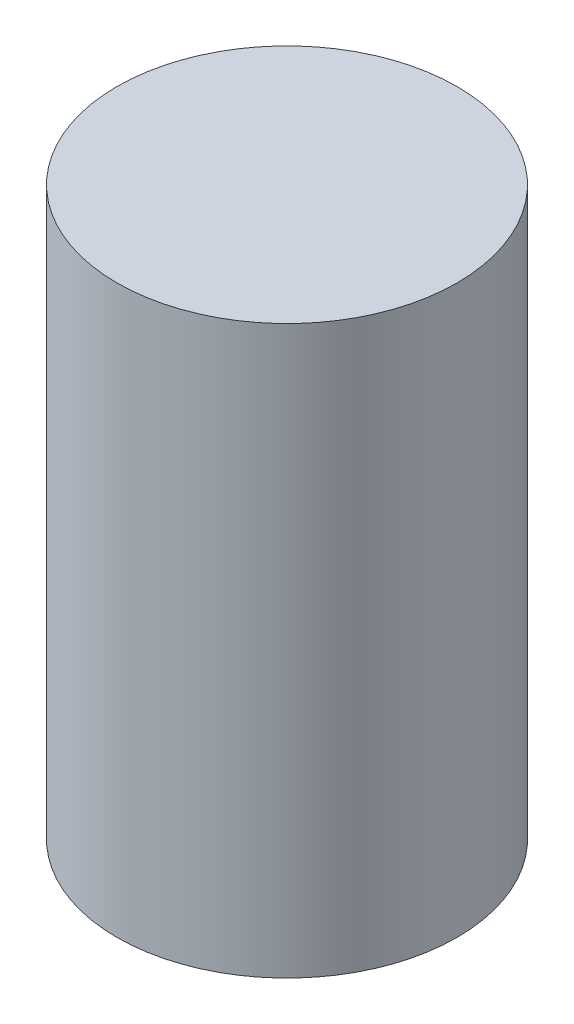
SolidWorks part; units mm, degrees
material "AISI 304"
ref_plane "前视基准面" through (0, 0, 0) normal (0, 0, 1) x (1, 0, 0)
ref_plane "上视基准面" through (0, 0, 0) normal (0, 1, 0) x (1, 0, 0)
ref_plane "右视基准面" through (0, 0, 0) normal (1, 0, 0) x (0, 0, -1)
sketch "草图1" plane through (0, 0, 0) normal (0, 1, 0) x (1, 0, 0)
  circle A0 centre (0, 0) radius 1.5
  dimension "D1" = 3
extrude "凸台-拉伸1" add sketch "草图1" along normal blind 5
